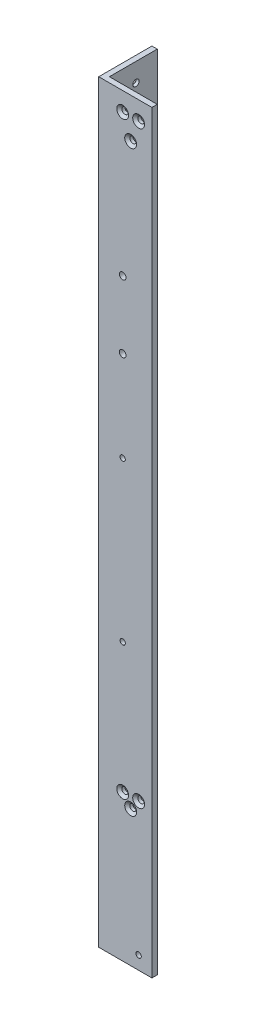
SolidWorks part; units mm, degrees
ref_plane "Front Plane" through (0, 0, 0) normal (0, 0, 1) x (1, 0, 0)
ref_plane "Top Plane" through (0, 0, 0) normal (0, 1, 0) x (1, 0, 0)
ref_plane "Right Plane" through (0, 0, 0) normal (1, 0, 0) x (0, 0, -1)
sketch "Sketch2" plane through (0, 0, 0) normal (0, 1, 0) x (1, 0, 0)
  line L0 (0, 31.75) -> (3.175, 31.75)
  line L1 (3.175, 31.75) -> (3.175, 3.175)
  line L2 (3.175, 3.175) -> (31.75, 3.175)
  line L3 (31.75, 3.175) -> (31.75, 0)
  line L4 (31.75, 0) -> (0, 0)
  line L5 (0, 0) -> (0, 31.75)
  point P9 (1.5875, 31.75)
  point P10 (31.75, 1.5875)
  dimension "D4" = 3.175
  dimension "D1" = 31.75
  dimension "D2" = 31.75
  dimension "D3" = 3.175
extrude "Boss-Extrude1" add sketch "Sketch2" along normal blind 450
sketch "FrontSideHoles-Sketch3" plane through (0, 0, 0) normal (0, 0, 1) x (1, 0, 0)
  line L0 (0, 0) -> (31.75, 0) construction
  line L1 (0, 450) -> (0, 0) construction
  circle A1 centre (19.05, 81.1125) radius 1.5875
  circle A2 centre (14.2875, 87.4625) radius 1.5875
  circle A3 centre (23.8125, 87.4625) radius 1.5875
  circle A4 centre (14.2875, 438.8875) radius 1.5875
  circle A6 centre (23.8125, 438.8875) radius 1.5875
  circle A7 centre (19.05, 426.1875) radius 1.5875
  circle A8 centre (14.2875, 354.1849) radius 2
  circle A9 centre (14.2875, 313.9849) radius 2
  circle A10 centre (14.2875, 260) radius 1.5875
  circle A11 centre (14.2875, 165) radius 1.5875
  circle A14 centre (23.8125, 7.9375) radius 1.5875
  dimension "D4" = 3.175
  dimension "D15" = 4
  dimension "D13" = 3.175
  dimension "D8" = 11.1125
  dimension "D11" = 40.2
  dimension "D6" = 165
  dimension "D10" = 95
  dimension "D2" = 14.2875
  dimension "D5" = 6.35
  dimension "D14" = 81.1125
  dimension "D7" = 12.7
  dimension "D16" = 14.2875
  dimension "D9" = 354.1849
  dimension "D17" = 19.05
  dimension "D3" = 23.8125
  dimension "D12" = 7.9375
sketch "LeftSideHoles-Sketch4" plane through (0, 0, 0) normal (-1, 0, 0) x (0, 0, 1)
  line L0 (-31.75, 450) -> (0, 450) construction
  line L1 (0, 450) -> (0, 0) construction
  line L3 (-31.75, 0) -> (0, 0) construction
  circle A0 centre (-23.8125, 81.1125) radius 1.5875
  circle A1 centre (-14.2875, 81.1125) radius 1.5875
  circle A2 centre (-19.05, 87.4625) radius 1.5875
  circle A4 centre (-19.05, 438.8875) radius 1.5875
  circle A6 centre (-23.8125, 426.1875) radius 1.5875
  circle A7 centre (-14.2875, 426.1875) radius 1.5875
  circle A8 centre (-23.8125, 341.2474) radius 1.5875
  circle A9 centre (-14.2875, 341.2474) radius 1.5875
  circle A10 centre (-23.8125, 306.3224) radius 1.5875
  circle A11 centre (-14.2875, 306.3224) radius 1.5875
  circle A12 centre (-23.8125, 7.9375) radius 1.5875
  circle A14 centre (-14.2875, 165) radius 1.5875
  circle A15 centre (-14.2875, 260) radius 1.5875
  circle A16 centre (-14.2875, 355) radius 1.5875
  dimension "D4" = 3.175
  dimension "D2" = 14.2875
  dimension "D5" = 6.35
  dimension "D7" = 12.7
  dimension "D3" = 81.1125
  dimension "D6" = 11.1125
  dimension "D10" = 7.9375
  dimension "D9" = 34.925
  dimension "D8" = 341.2474
  dimension "D12" = 165
  dimension "D13" = 95
  dimension "D14" = 95
  dimension "D15" = 19.05
  dimension "D11" = 23.8125
extrude "FrontSideHoles-Cut-Extrude1" cut sketch "FrontSideHoles-Sketch3" against normal blind 3.175
extrude "LeftSideHoles-Cut-Extrude2" cut sketch "LeftSideHoles-Sketch4" against normal blind 3.175
sketch "Sketch3" plane through (0, 0, 0) normal (0, 0, 1) x (1, 0, 0)
  point P0 (14.2875, 87.4625)
  point P3 (19.05, 81.1125)
  point P6 (23.8125, 87.4625)
  point P9 (19.05, 426.1875)
  point P12 (14.2875, 438.8875)
  point P15 (23.8125, 438.8875)
hole_wizard "CSK for #6 Flat Head Machine Screw (100)1" positions "Sketch3" profile "Sketch4" countersink size "#6" standard "ANSI Inch" end condition through all
sketch "Sketch4" plane through (14.2875, 87.4625, 0) normal (1, 0, 0) x (0, -1, 0)
  line L0 (0, 0) -> (0, 31.75)
  line L1 (0, 31.75) -> (1.8986, 31.75)
  line L2 (1.8986, 31.75) -> (1.8986, 1.38)
  line L3 (1.8986, 1.38) -> (3.5433, 0)
  line L5 (3.5433, 0) -> (0, 0)
  line L6 (-1.8986, 1.38) -> (-3.5433, 0) construction
  line L11 (0, -6.35) -> (0, 107.95) construction
  dimension "Thru Hole Dia." = 3.7973
  dimension "Thru Hole Depth" = 31.75
  dimension "Near C'Sink Dia." = 7.0866
  dimension "Near C'Sink Angle" = 100
sketch "Sketch8" plane through (0, 0, 0) normal (-1, 0, 0) x (0, 0, 1)
  point P0 (-19.05, 87.4625)
  point P3 (-23.8125, 81.1125)
  point P6 (-14.2875, 81.1125)
  point P9 (-23.8125, 341.2474)
  point P12 (-14.2875, 341.2474)
  point P15 (-14.2875, 306.3224)
  point P18 (-23.8125, 306.3224)
  point P21 (-23.8125, 426.1875)
  point P24 (-14.2875, 426.1875)
  point P27 (-19.05, 438.8875)
hole_wizard "CSK for #6 Flat Head Machine Screw (100)2" positions "Sketch8" profile "Sketch9" countersink size "#6" standard "ANSI Inch" end condition through all
sketch "Sketch9" plane through (0, 87.4625, -19.05) normal (0, 1, 0) x (0, 0, 1)
  line L0 (0, 0) -> (0, 31.75)
  line L1 (0, 31.75) -> (1.8986, 31.75)
  line L2 (1.8986, 31.75) -> (1.8986, 1.38)
  line L3 (1.8986, 1.38) -> (3.5433, 0)
  line L5 (3.5433, 0) -> (0, 0)
  line L6 (-1.8986, 1.38) -> (-3.5433, 0) construction
  line L11 (0, -6.35) -> (0, 107.95) construction
  dimension "Thru Hole Dia." = 3.7973
  dimension "Thru Hole Depth" = 31.75
  dimension "Near C'Sink Dia." = 7.0866
  dimension "Near C'Sink Angle" = 100
equation "\"RailThickness\"= .125in'Spec"
equation "\"VSWidth\"= 1.25in'Spec"
equation "\"VSHeight\"= 1.25in'Spec"
equation "\"VSLength\"= 450mm"
equation "\"HoleOffsetFromEdge\"= \"RailThickness\" * 2.5"
equation "\"HoleOffsetFromSide\"= \"RailThickness\" * 3.5"
equation "\"LegHeight\"= 70mm'Space needed for PSU/Stepper/Electronics"
equation "\"VSBottomSideRailHoleY1FromBottomOfLowerRail\"= \"V1 BottomOfLowerRail\" + \"HoleOffsetFromSide\"'Equals 81.1125"
equation "\"VSSideRailHoleX1FromSide\"= \"HoleOffsetFromSide\" + \"RailThickness\""
equation "\"FasteningHoleDiameter\"= .125in"
equation "\"VSBottomSideRailHoleY2FromY1\"= \"LowerRailHeight\" - \"HoleOffsetFromSide\" - \"HoleOffsetFromEdge\"'Equals 6.35"
equation "\"VSTopSideRailHoleY1FromEdge\"= \"HoleOffsetFromEdge\" + \"RailThickness\""
equation "\"D4@FrontSideHoles-Sketch3\" = \"FasteningHoleDiameter\""
equation "\"D1@Boss-Extrude1\"=\"VSLength\""
equation "\"D4@LeftSideHoles-Sketch4\" = \"FasteningHoleDiameter\""
equation "\"D3@LeftSideHoles-Sketch4\"= \"VSBottomSideRailHoleY1FromBottomOfLowerRail\""
equation "\"D8@FrontSideHoles-Sketch3\" = \"VSTopSideRailHoleY1FromEdge\""
equation "\"D6@LeftSideHoles-Sketch4\" = \"VSTopSideRailHoleY1FromEdge\""
equation "\"VSMidSideRailHoleY1FromV8TopOfMidSideRail\"= \"V8 ToTopOfMidSideRail\" - \"HoleOffsetFromEdge\"'Equals 341.24737"
equation "\"LowerRailHeight\"= 1.00in"
equation "\"D1@Sketch2\"=\"VSHeight\""
equation "\"D2@Sketch2\"=\"VSWidth\""
equation "\"TopRailHeight\"= 1.25in"
equation "\"MidLeftOrRightSideRailHeight\"= 2.0in"
equation "\"D10@LeftSideHoles-Sketch4\"=\"HoleOffsetFromEdge\""
equation "\"VSMidSideRailHoleY2FromY1\"= \"MidLeftOrRightSideRailHeight\" - \"HoleOffsetFromEdge\" * 2'Equals 34.925"
equation "\"D9@LeftSideHoles-Sketch4\"=\"VSMidSideRailHoleY2FromY1\""
equation "\"VSSideRailHoleX2FromSide\"= \"VSWidth\" - \"HoleOffsetFromEdge\""
equation "\"VSTopSideRailHoleY2FromY1\"= \"TopRailHeight\" - \"VSTopSideRailHoleY1FromEdge\" - \"HoleOffsetFromEdge\"'Equals 12.7"
equation "\"D7@LeftSideHoles-Sketch4\"=\"VSTopSideRailHoleY2FromY1\""
equation "\"BeltTensionerInnerHeight\"= \"20TGT2PulleyWidth\" * 2 + \"1mmSpacer\" * 3"
equation "\"20TGT2PulleyWidth\"= 8.7mm'The STL of the Pulley in the diagram is a bit larger"
equation "\"1mmSpacer\"= 1mm"
equation "\"BeltTensionerHeight\"= 60mm"
equation "\"D11@FrontSideHoles-Sketch3\"=\"VSBeltTensionerHoleY2FromY1\""
equation "\"VSBeltTensionerHoleY1ToAlignWithYAxisGantryBlockUpperPulley\"= \"V5 ToBottomOfXAxisLinearRail\" - \"DistanceFromXAxisLinearRailBottomAndTopGantryPulley\" + \"DistanceFromBeltTensionerTopPulleyToBeltTensionertop\" - \"BeltTensionerMountingHoleOffsetFromTopOrBottom\"'Equals 354.18487"
equation "\"VSBeltTensionerHoleY2FromY1\"= \"BeltTensionerHeight\" - \"BeltTensionerMountingHoleOffsetFromTopOrBottom\" * 2"
equation "\"V1 BottomOfLowerRail\"= \"LegHeight\""
equation "\"StepperShaftLength\"= 24mm'Pulley will be attached to the end"
equation "\"ZAxisLeadScrewLength\"= 200mm"
equation "\"LM8UUHeight\"= 24mm'Spec"
equation "\"V2 ToBedAtTopOfZAxis\"= \"V1 BottomOfLowerRail\" - \"LowerEnclosureThickness\" + \"StepperShaftLength\" + \"ZAxisLeadScrewLength\" - \"LM8UUHeight\" / 2'Equals 277"
equation "\"HotEndToTopOfXAxisGB\"= 71.68487mm'Equals 71.68487. Measured after installed onto X-Axis linear rail guide block"
equation "\"TopOfGBToBottomOfLinearRail\"= \"LinearGBWidth\" / 2 + \"LinearRailWidth\" / 2'Equals 19.5"
equation "\"LinearGBWidth\"= 27mm'Spec"
equation "\"V5 ToBottomOfXAxisLinearRail\"= \"V4 ToTopOfBuildPlate/HotEndTip\" + \"HotEndToTopOfXAxisGB\" - \"TopOfGBToBottomOfLinearRail\"'Equals 352.18487"
equation "\"LinearRailWidth\"= 12mm'Spec"
equation "\"V6 ToMiddleOfYAxisGantryBlock\"= \"V5 ToBottomOfXAxisLinearRail\" - \"GABHeight\" / 2'Equals 334.18487"
equation "\"GABUpperHeight\"= 4mm"
equation "\"GABMidWallHeight\"= 28mm'Must equal 28 or changes alignment"
equation "\"D8@LeftSideHoles-Sketch4\"= \"VSMidSideRailHoleY1FromV8TopOfMidSideRail\""
equation "\"BedToBuildPlateStandoffLength\"= 15mm"
equation "\"BuildPlateHeight\"= 8mm'Spec"
equation "\"V4 ToTopOfBuildPlate/HotEndTip\"= \"V2 ToBedAtTopOfZAxis\" + \"BedToBuildPlateStandoffLength\" + \"BuildPlateHeight\""
equation "\"V8 ToTopOfMidSideRail\"= \"V6 ToMiddleOfYAxisGantryBlock\" + \"MidSideRailVerticalOffset\"'Equals 349.18487"
equation "\"VSEnclosureOffsets\"= ( \"VSLength\" - \"LegHeight\" ) / 4"
equation "\"D6@FrontSideHoles-Sketch3\"=\"LegHeight\" + \"VSEnclosureOffsets\""
equation "\"D10@FrontSideHoles-Sketch3\"=\"VSEnclosureOffsets\""
equation "\"D13@LeftSideHoles-Sketch4\"=\"VSEnclosureOffsets\""
equation "\"D12@LeftSideHoles-Sketch4\"=\"LegHeight\" + \"VSEnclosureOffsets\""
equation "\"D2@FrontSideHoles-Sketch3\"=\"VSSideRailHoleX1FromSide\""
equation "\"D5@FrontSideHoles-Sketch3\"=\"VSBottomSideRailHoleY2FromY1\""
equation "\"D14@FrontSideHoles-Sketch3\"=\"VSBottomSideRailHoleY1FromBottomOfLowerRail\""
equation "\"D7@FrontSideHoles-Sketch3\"=\"VSTopSideRailHoleY2FromY1\""
equation "\"D5@LeftSideHoles-Sketch4\"=\"VSBottomSideRailHoleY2FromY1\""
equation "\"BeltTensionerMountingHoleDiameter\"= 4.0mm"
equation "\"D15@FrontSideHoles-Sketch3\"=\"BeltTensionerMountingHoleDiameter\""
equation "\"LowerEnclosureThickness\"= 5mm"
equation "\"GABLowerHeight\"= 4mm"
equation "\"GABHeight\"= \"GABLowerHeight\" + \"GABMidWallHeight\" + \"GABUpperHeight\""
equation "\"D14@LeftSideHoles-Sketch4\"=\"VSEnclosureOffsets\""
equation "\"BeltTensionerMountingHoleOffsetFromTopOrBottom\"= ( \"BeltTensionerHeight\" - \"BeltTensionerInnerHeight\" ) / 4"
equation "\"D13@FrontSideHoles-Sketch3\"=\"FasteningHoleDiameter\""
equation "\"VSBeltTensionerXMountingHoleOffsetFromSide\"= \"BeltTensionerMountingHoleOffsetFromEdge\" + \"RailThickness\" * 2"
equation "\"BeltTensionerMountingHoleOffsetFromEdge\"= \"HoleOffsetFromEdge\""
equation "\"D16@FrontSideHoles-Sketch3\"=\"VSBeltTensionerXMountingHoleOffsetFromSide\""
equation "\"MidSideRailVerticalOffset\"= \"LinearRailWidth\" + 3mm'Allows space for RodStabilizer to attach to bottom of MidSideRail"
equation "\"GABRiserBossOffset\"= 0.4mm'Aligns Pulleys inside edges to be 2.5mm (.5mm apart top to bottom)"
equation "\"GABMidShortRiserHeight\"= \"GABMidWallHeight\" / 2 - \"20TGT2PulleyWidth\"'Equals 5.3"
equation "\"7mmx1mmSpacerHeight\"= 1mm"
equation "\"D9@FrontSideHoles-Sketch3\"=\"VSBeltTensionerHoleY1ToAlignWithYAxisGantryBlockUpperPulley\""
equation "\"DistanceFromXAxisLinearRailBottomAndTopGantryPulley\"= \"GABUpperHeight\" + \"GABMidShortRiserHeight\" - \"GABRiserBossOffset\"'Equals 8.9"
equation "\"DistanceFromBeltTensionerTopPulleyToBeltTensionertop\"= \"7mmx1mmSpacerHeight\" + \"BeltTensionerTopHeight\"'Equals 20.8"
equation "\"BeltTensionerTopHeight\"= ( \"BeltTensionerHeight\" - \"BeltTensionerInnerHeight\" ) / 2'Equals 19.8"
equation "\"VSMidSideRailHoleXFromSideToCenter\"= \"RailThickness\" * 6"
equation "\"D17@FrontSideHoles-Sketch3\"=\"VSMidSideRailHoleXFromSideToCenter\""
equation "\"D2@LeftSideHoles-Sketch4\"=\"VSSideRailHoleX1FromSide\""
equation "\"D3@FrontSideHoles-Sketch3\"=\"VSSideRailHoleX2FromSide\""
equation "\"D12@FrontSideHoles-Sketch3\"=\"HoleOffsetFromEdge\""
equation "\"D11@LeftSideHoles-Sketch4\"=\"VSSideRailHoleX2FromSide\""
equation "\"D15@LeftSideHoles-Sketch4\"=\"VSMidSideRailHoleXFromSideToCenter\""
